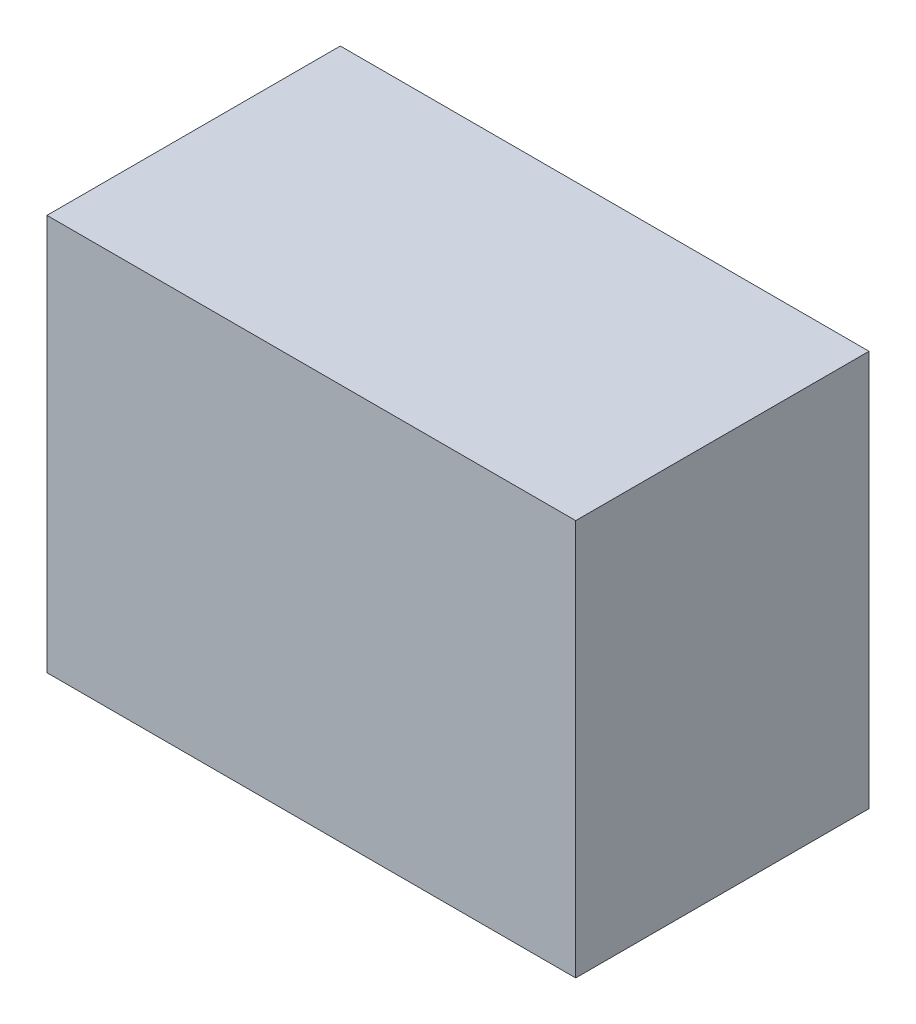
SolidWorks part; units mm, degrees
ref_plane "Front Plane" through (0, 0, 0) normal (0, 0, 1) x (1, 0, 0)
ref_plane "Top Plane" through (0, 0, 0) normal (0, 1, 0) x (1, 0, 0)
ref_plane "Right Plane" through (0, 0, 0) normal (1, 0, 0) x (0, 0, -1)
sketch "Sketch1" plane through (0, 0, 0) normal (0, 0, 1) x (1, 0, 0)
  line L1 (-36.7814, 30.0638) -> (31.7157, 30.0638)
  line L2 (-36.7814, 30.0638) -> (-36.7814, -21.2539)
  line L3 (-36.7814, -21.2539) -> (31.7157, -21.2539)
  line L4 (31.7157, 30.0638) -> (31.7157, -21.2539)
extrude "Boss-Extrude1" add sketch "Sketch1" along normal blind 38
